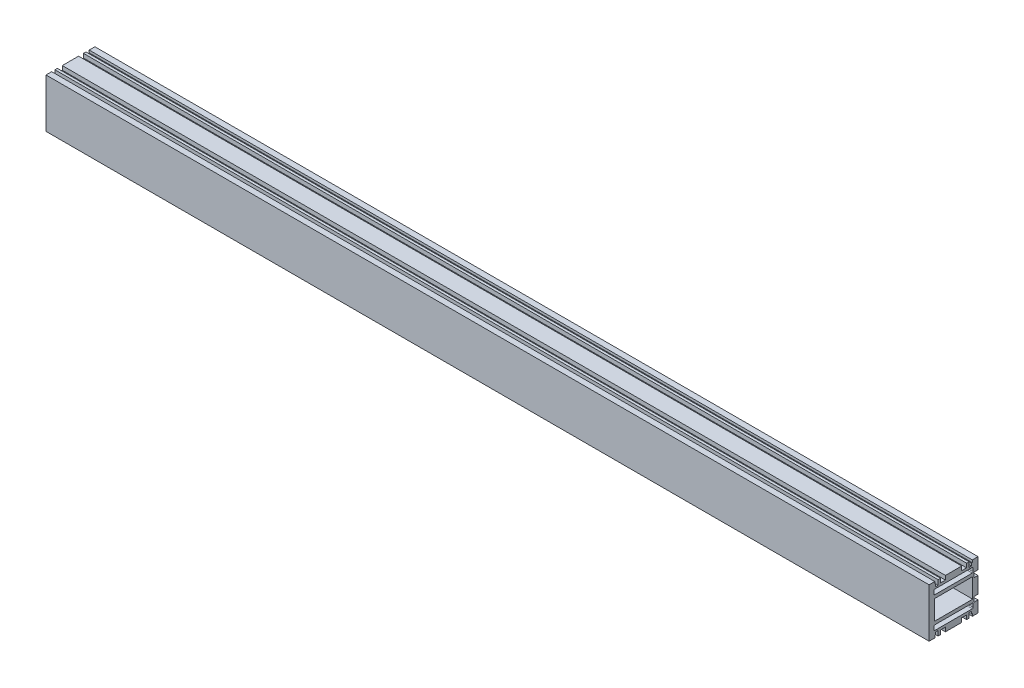
SolidWorks part; units mm, degrees
ref_plane "前视基准面" through (0, 0, 0) normal (0, 0, 1) x (1, 0, 0)
ref_plane "上视基准面" through (0, 0, 0) normal (0, 1, 0) x (1, 0, 0)
ref_plane "右视基准面" through (0, 0, 0) normal (1, 0, 0) x (0, 0, -1)
sketch "草图1" plane through (0, 0, 0) normal (1, 0, 0) x (0, 0, -1)
  line L0 (-15, 15) -> (15, -15) construction
  line L1 (-15, 15) -> (-11.5, 15)
  line L2 (-15, 15) -> (-15, -15)
  line L3 (-15, -15) -> (-11.5, -15)
  line L4 (15, 15) -> (15, 8)
  line L5 (15, 15) -> (-15, -15) construction
  line L6 (-11.5, 15) -> (-11.5, 13.5)
  line L7 (-11.5, 13.5) -> (-11, 13.5)
  line L8 (-11, 13.5) -> (-11, 12)
  line L9 (-11, 12) -> (-9.5, 12)
  line L10 (-9.5, 12) -> (-9.5, 15)
  line L11 (-9.5, 15) -> (-8, 15)
  line L12 (-8, 15) -> (-8, 12.5)
  line L13 (-8, 12.5) -> (-5, 12.5)
  line L14 (-5, 12.5) -> (-5, 15)
  line L15 (-5, 15) -> (5, 15)
  line L16 (0, 21.5201) -> (0, -18.309) construction
  line L17 (0, 55) -> (0, -55) construction
  line L18 (5, 12.5) -> (5, 15)
  line L19 (8, 12.5) -> (5, 12.5)
  line L20 (8, 15) -> (8, 12.5)
  line L21 (9.5, 15) -> (8, 15)
  line L22 (9.5, 12) -> (9.5, 15)
  line L23 (11, 12) -> (9.5, 12)
  line L24 (11, 13.5) -> (11, 12)
  line L25 (11.5, 13.5) -> (11, 13.5)
  line L26 (11.5, 15) -> (11.5, 13.5)
  line L27 (8, 15) -> (9.5, 15)
  line L28 (11.5, 15) -> (15, 15)
  line L29 (-19.8303, 0) -> (22.13, 0) construction
  line L30 (55, 0) -> (-55, 0) construction
  line L31 (8, -15) -> (9.5, -15)
  line L32 (11.5, -15) -> (11.5, -13.5)
  line L33 (11.5, -13.5) -> (11, -13.5)
  line L34 (11, -13.5) -> (11, -12)
  line L35 (11, -12) -> (9.5, -12)
  line L36 (9.5, -12) -> (9.5, -15)
  line L37 (9.5, -15) -> (8, -15)
  line L38 (8, -15) -> (8, -12.5)
  line L39 (8, -12.5) -> (5, -12.5)
  line L40 (5, -12.5) -> (5, -15)
  line L41 (-5, -15) -> (5, -15)
  line L42 (-5, -12.5) -> (-5, -15)
  line L43 (-8, -12.5) -> (-5, -12.5)
  line L44 (-8, -15) -> (-8, -12.5)
  line L45 (-9.5, -15) -> (-8, -15)
  line L46 (-9.5, -12) -> (-9.5, -15)
  line L47 (-11, -12) -> (-9.5, -12)
  line L48 (-11, -13.5) -> (-11, -12)
  line L49 (-11.5, -13.5) -> (-11, -13.5)
  line L50 (-11.5, -15) -> (-11.5, -13.5)
  line L51 (-9.5, -15) -> (-8, -15)
  line L52 (-5, -15) -> (5, -15)
  line L53 (8, -15) -> (9.5, -15)
  line L54 (11.5, -15) -> (15, -15)
  line L55 (15, 8) -> (12.5, 8)
  line L56 (12.5, 8) -> (12.5, 5)
  line L57 (12.5, 5) -> (15, 5)
  line L58 (12.5, -5) -> (15, -5)
  line L59 (12.5, -8) -> (12.5, -5)
  line L60 (15, -8) -> (12.5, -8)
  line L61 (15, 5) -> (15, -5)
  line L62 (15, -8) -> (15, -15)
  line L63 (12, -10.5) -> (12, -8.5)
  line L64 (-11.5, 11) -> (11.5, 11)
  line L65 (-12, 10.5) -> (-12, 8.5)
  line L66 (-11.5, 8) -> (11.5, 8)
  line L67 (12, 10.5) -> (12, 8.5)
  line L68 (-11.5, -8) -> (11.5, -8)
  line L69 (-12, -10.5) -> (-12, -8.5)
  line L70 (-11.5, -11) -> (11.5, -11)
  line L72 (-11.75, 6) -> (11.75, 6)
  line L73 (-11.75, 6) -> (-11.75, -6)
  line L74 (-11.75, -6) -> (11.75, -6)
  line L75 (11.75, 6) -> (11.75, -6)
  arc A0 (12, 8.5) -> (11.5, 8) centre (11.5, 8.5) cw
  arc A1 (11.5, 11) -> (12, 10.5) centre (11.5, 10.5) cw
  arc A2 (-11.5, 11) -> (-12, 10.5) centre (-11.5, 10.5) ccw
  arc A3 (-11.5, 8) -> (-12, 8.5) centre (-11.5, 8.5) cw
  arc A8 (-11.5, -8) -> (-12, -8.5) centre (-11.5, -8.5) ccw
  arc A9 (-11.5, -11) -> (-12, -10.5) centre (-11.5, -10.5) cw
  arc A10 (11.5, -11) -> (12, -10.5) centre (11.5, -10.5) ccw
  arc A11 (12, -8.5) -> (11.5, -8) centre (11.5, -8.5) ccw
  point P69 (12, 11)
  point P72 (-12, 11)
  point P77 (-11, -13.5)
  point P80 (11, -13.5)
  point P83 (11, 13.5)
  point P86 (-11, 13.5)
  point P99 (-12, -11)
  point P100 (12, -11)
  dimension "D17" = 0.5
  dimension "D1" = 3.5
  dimension "D2" = 1.5
  dimension "D3" = 0.5
  dimension "D4" = 1.5
  dimension "D5" = 3
  dimension "D6" = 30
  dimension "D7" = 30
  dimension "D8" = 1.5
  dimension "D9" = 2.5
  dimension "D10" = 3
  dimension "D11" = 2.5
  dimension "D12" = 7
  dimension "D13" = 3
  dimension "D14" = 4
  dimension "D15" = 3
  dimension "D16" = 24
  dimension "D19" = 23.5
  dimension "D20" = 12
extrude "凸台-拉伸1" add sketch "草图1" along normal mid plane 542
hole_wizard "M6 螺纹孔1" positions "草图3" profile "草图2" tap size "M6" standard "GB"
sketch "草图3" plane through (0, -15, 0) normal (0, -1, 0) x (-1, 0, 0)
  point P0 (-236, 0)
  point P3 (-251, 0)
  point P6 (251, 0)
  point P9 (236, 0)
sketch "草图2" plane through (236, -15, 0) normal (1, 0, 0) x (0, 0, -1)
  line L0 (0, 0) -> (0, 20.5022)
  line L1 (0, 20.5022) -> (2.5, 19)
  line L2 (2.5, 19) -> (2.5, 0)
  line L5 (2.5, 0) -> (0, 0)
  line L10 (0, 20.5022) -> (-2.5, 19) construction
  line L11 (0, -6.35) -> (0, 107.95) construction
  dimension "螺纹孔钻头直径" = 5
  dimension "螺纹孔钻头深度" = 19
  dimension "导头角度" = 118
cosmetic thread "孔螺蚊线1" parameters "D1"=9, "D2"=6
cosmetic thread "孔螺蚊线2" parameters "D1"=9, "D2"=6
cosmetic thread "孔螺蚊线3" parameters "D1"=9, "D2"=6
cosmetic thread "孔螺蚊线4" parameters "D1"=9, "D2"=6
hole_wizard "M6 螺纹孔2" positions "草图5" profile "草图4" tap size "M6" standard "GB"
sketch "草图5" plane through (0, 0, -15) normal (0, 0, -1) x (-1, 0, 0)
  point P0 (236, 0)
  point P3 (251, 0)
sketch "草图4" plane through (-236, 0, -15) normal (1, 0, 0) x (0, 1, 0)
  line L0 (0, 0) -> (0, 20.5022)
  line L1 (0, 20.5022) -> (2.5, 19)
  line L2 (2.5, 19) -> (2.5, 0)
  line L5 (2.5, 0) -> (0, 0)
  line L10 (0, 20.5022) -> (-2.5, 19) construction
  line L11 (0, -6.35) -> (0, 107.95) construction
  dimension "螺纹孔钻头直径" = 5
  dimension "螺纹孔钻头深度" = 19
  dimension "导头角度" = 118
cosmetic thread "孔螺蚊线5" parameters "D1"=3.25, "D2"=6
cosmetic thread "孔螺蚊线6" parameters "D1"=3.25, "D2"=6
hole_wizard "M4 螺纹孔1" positions "草图7" profile "草图6" tap size "M4" standard "GB"
sketch "草图7" plane through (0, 0, -15) normal (0, 0, -1) x (-1, 0, 0)
  line L0 (-271, -15) -> (271, -15) construction
  line L1 (-271, 5) -> (-271, -5) construction
  line L2 (271, -8) -> (271, -15) construction
  line L3 (-271, -15) -> (271, -15) construction
  point P0 (-258, 0)
  point P2 (-60.5, 0)
  point P9 (-21.5, 0)
  point P11 (201, 0)
  point P23 (170.119, 33.5112)
  dimension "D1" = 15
  dimension "D2" = 15
  dimension "D3" = 13
  dimension "D4" = 210.5
  dimension "D5" = 15
  dimension "D6" = 292.5
  dimension "D7" = 15
  dimension "D8" = 70
sketch "草图6" plane through (258, 0, -15) normal (1, 0, 0) x (0, 1, 0)
  line L0 (0, 0) -> (0, 12.4914)
  line L1 (0, 12.4914) -> (1.65, 11.5)
  line L2 (1.65, 11.5) -> (1.65, 0)
  line L5 (1.65, 0) -> (0, 0)
  line L10 (0, 12.4914) -> (-1.65, 11.5) construction
  line L11 (0, -6.35) -> (0, 107.95) construction
  dimension "螺纹孔钻头直径" = 3.3
  dimension "螺纹孔钻头深度" = 11.5
  dimension "导头角度" = 118
cosmetic thread "孔螺蚊线7" parameters "D1"=3.25, "D2"=4
cosmetic thread "孔螺蚊线8" parameters "D1"=3.25, "D2"=4
cosmetic thread "孔螺蚊线9" parameters "D1"=3.25, "D2"=4
cosmetic thread "孔螺蚊线10" parameters "D1"=3.25, "D2"=4
